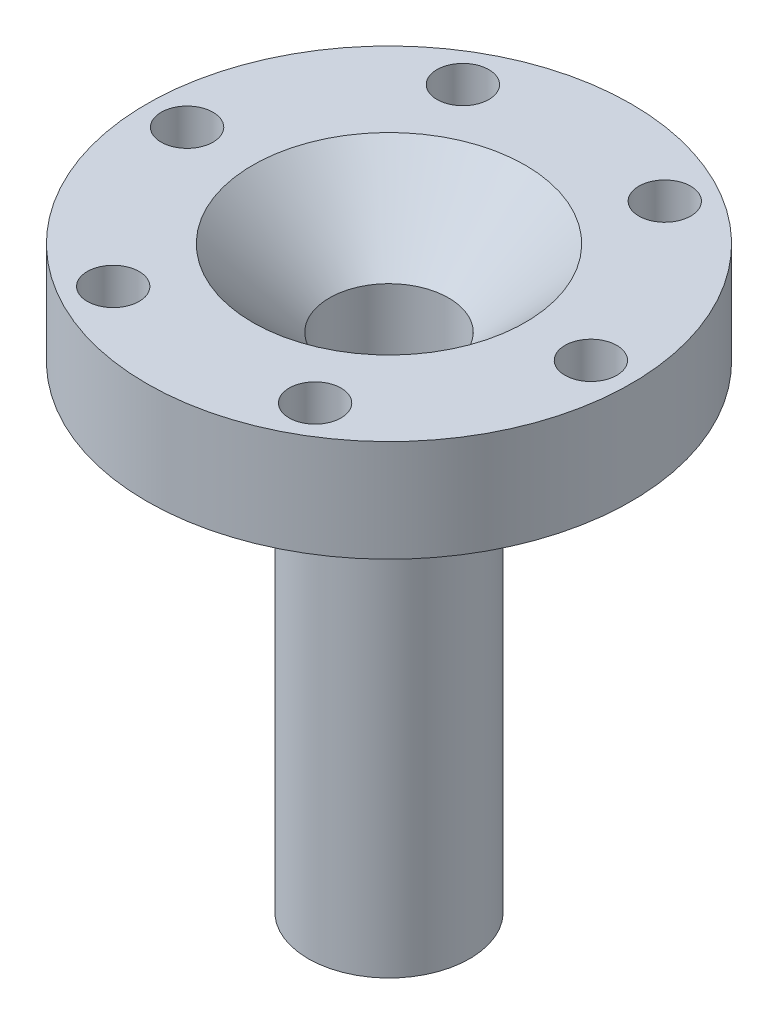
SolidWorks part; units mm, degrees
material "AISI Type 316L stainless steel"
ref_plane "Front Plane" through (0, 0, 0) normal (0, 0, 1) x (1, 0, 0)
ref_plane "Top Plane" through (0, 0, 0) normal (0, 1, 0) x (1, 0, 0)
ref_plane "Right Plane" through (0, 0, 0) normal (1, 0, 0) x (0, 0, -1)
sketch "Sketch1" plane through (0, 0, 0) normal (0, 0, 1) x (1, 0, 0)
  line L0 (0, 0) -> (0, -29.8554) construction
  line L1 (7.5, -72.82) -> (7.5, -9.645)
  line L2 (7.5, -9.645) -> (17.145, 0)
  line L3 (17.145, 0) -> (30.48, 0)
  line L4 (30.48, 0) -> (30.48, -12.82)
  line L5 (30.48, -12.82) -> (10.16, -12.82)
  line L6 (10.16, -12.82) -> (10.16, -72.82)
  line L7 (10.16, -72.82) -> (7.5, -72.82)
  dimension "D1" = 20.32
  dimension "D2" = 15
  dimension "D3" = 60
  dimension "D4" = 45
  dimension "D5" = 34.29
  dimension "D6" = 60.96
  dimension "D7" = 3.175
revolve "Revolve1" add sketch "Sketch1" angle 360 about L0
hole_wizard "1/4 Clearance Hole1" positions "Sketch3" profile "Sketch4" hole size "1/4" standard "ANSI Inch" end condition through all
sketch "Sketch3" plane through (0, 0, 0) normal (0, 1, 0) x (1, 0, 0)
  line L0 (25.4, 0) -> (0, 0) construction
  point P0 (25.4, 0)
  dimension "D1" = 25.4
sketch "Sketch4" plane through (25.4, 0, 0) normal (1, 0, 0) x (0, 0, 1)
  line L0 (0, 0) -> (0, 72.82)
  line L1 (0, 72.82) -> (3.2639, 72.82)
  line L2 (3.2639, 72.82) -> (3.2639, 0)
  line L5 (3.2639, 0) -> (0, 0)
  line L11 (0, -6.35) -> (0, 107.95) construction
  dimension "Thru Hole Dia." = 6.5278
  dimension "Thru Hole Depth" = 72.82
pattern_circular "CirPattern1" count 6 over 360 about axis through (0, 0, 0) along (0, 1, 0) of "1/4 Clearance Hole1"
